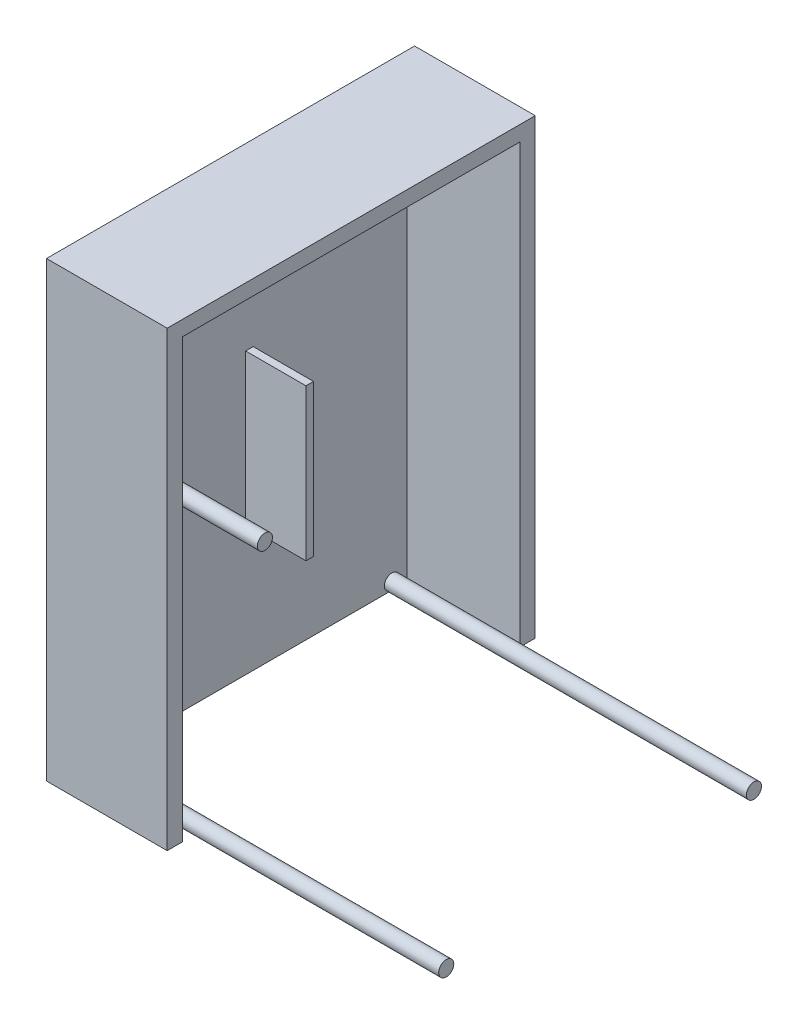
SolidWorks part; units mm, degrees
ref_plane "Front Plane" through (0, 0, 0) normal (0, 0, 1) x (1, 0, 0)
ref_plane "Top Plane" through (0, 0, 0) normal (0, 1, 0) x (1, 0, 0)
ref_plane "Right Plane" through (0, 0, 0) normal (1, 0, 0) x (0, 0, -1)
sketch "Sketch1" plane through (0, 0, 0) normal (1, 0, 0) x (0, 0, -1)
  line L1 (-71.6415, 87.4398) -> (70.5985, 87.4398)
  line L2 (-71.6415, 87.4398) -> (-71.6415, -96.7102)
  line L3 (-71.6415, -96.7102) -> (70.5985, -96.7102)
  line L4 (70.5985, 87.4398) -> (70.5985, -96.7102)
  line L5 (-77.9915, -96.7102) -> (76.9485, -96.7102)
  line L6 (-77.9915, -96.7102) -> (-77.9915, 93.7898)
  line L7 (-77.9915, 93.7898) -> (76.9485, 93.7898)
  line L8 (76.9485, -96.7102) -> (76.9485, 93.7898)
  dimension "D1" = 142.24
  dimension "D2" = 184.15
  dimension "D3" = 6.35
  dimension "D4" = 6.35
  dimension "D5" = 6.35
extrude "Boss-Extrude1" add sketch "Sketch1" along normal blind 3.175 contours L4 L1 L2 L3
sketch "Sketch2" plane through (0, 0, 0) normal (-1, 0, 0) x (0, 0, 1)
  line L0 (71.6415, -96.7102) -> (77.9915, -96.7102)
  line L1 (-76.9485, 93.7898) -> (77.9915, 93.7898)
  line L2 (-76.9485, 93.7898) -> (-76.9485, -96.7102)
  line L3 (-76.9485, -96.7102) -> (-70.5985, -96.7102)
  line L4 (77.9915, 93.7898) -> (77.9915, -96.7102)
  line L5 (-70.5985, 87.4398) -> (71.6415, 87.4398)
  line L6 (-70.5985, 87.4398) -> (-70.5985, -96.7102)
  line L8 (71.6415, 87.4398) -> (71.6415, -96.7102)
extrude "Boss-Extrude2" add sketch "Sketch2" against normal blind 50.8
sketch "Sketch3" plane through (3.175, 0, 0) normal (1, 0, 0) x (0, 0, -1)
  line L0 (-71.6415, -96.7102) -> (70.5985, -96.7102) construction
  line L1 (-71.6415, 87.4398) -> (-71.6415, -96.7102) construction
  line L2 (70.5985, 87.4398) -> (70.5985, -96.7102) construction
  circle A0 centre (-65.2915, -93.5352) radius 3.175
  circle A1 centre (64.2485, -93.5352) radius 3.175
  dimension "D1" = 6.35
  dimension "D4" = 6.35
  dimension "D2" = 3.175
  dimension "D3" = 6.35
  dimension "D5" = 3.175
  dimension "D6" = 6.35
extrude "Boss-Extrude3" add sketch "Sketch3" along normal blind 152.4
sketch "Sketch4" plane through (3.175, 0, 0) normal (1, 0, 0) x (0, 0, -1)
  line L0 (-71.6415, 87.4398) -> (70.5985, 87.4398) construction
  circle A0 centre (-36.8453, -4.6352) radius 3.175
  point P4 (-0.5215, 87.4398)
  dimension "D1" = 6.35
  dimension "D2" = 92.075
  dimension "D3" = 36.3238
extrude "Boss-Extrude5" add sketch "Sketch4" along normal blind 47.625
sketch "Sketch5" plane through (3.175, 0, 0) normal (1, 0, 0) x (0, 0, -1)
  line L1 (2.6535, 21.3484) -> (5.8285, 21.3484)
  line L2 (2.6535, 21.3484) -> (2.6535, -42.4597)
  line L3 (2.6535, -42.4597) -> (5.8285, -42.4597)
  line L4 (5.8285, 21.3484) -> (5.8285, -42.4597)
  line L5 (70.5985, 87.4398) -> (70.5985, -96.7102) construction
  dimension "D1" = 3.175
  dimension "D2" = 64.77
extrude "Boss-Extrude6" add sketch "Sketch5" along normal blind 25.4
